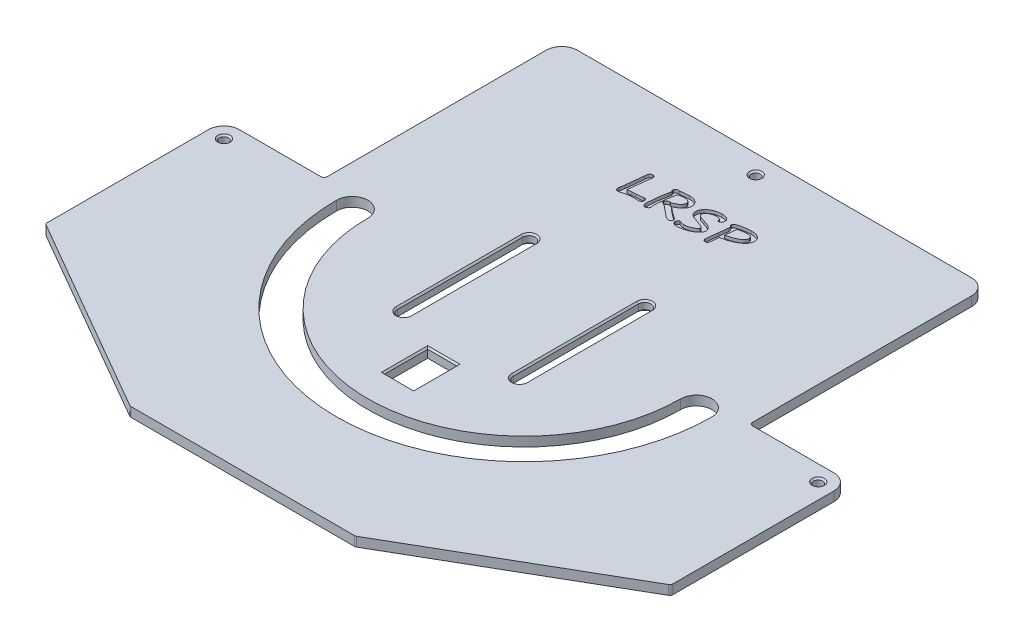
SolidWorks part; units mm, degrees
ref_plane "前视基准面" through (0, 0, 0) normal (0, 0, 1) x (1, 0, 0)
ref_plane "上视基准面" through (0, 0, 0) normal (0, 1, 0) x (1, 0, 0)
ref_plane "右视基准面" through (0, 0, 0) normal (1, 0, 0) x (0, 0, -1)
other "Configuration Table"
sketch "草图1" plane through (0, 0, 0) normal (0, 1, 0) x (1, 0, 0)
  line L11 (-100, -81) -> (-100, -132.4722)
  line L12 (-99.5, -133.3383) -> (-36.2321, -169.866)
  line L13 (-35.7321, -170) -> (35.7321, -170)
  line L14 (36.2321, -169.866) -> (99.5, -133.3383)
  line L15 (100, -132.4722) -> (100, -81)
  line L16 (95, -76) -> (69, -76)
  line L17 (68, -75) -> (68, -5)
  line L18 (63, 0) -> (-63, 0)
  line L19 (-68, -5) -> (-68, -75)
  line L20 (-69, -76) -> (-95, -76)
  circle A13 centre (95, -81) radius 1.45
  circle A14 centre (0, -6) radius 1.45
  circle A15 centre (-95, -81) radius 1.45
  arc A16 (-100, -132.4722) -> (-99.5, -133.3383) centre (-99, -132.4722) ccw
  arc A17 (-36.2321, -169.866) -> (-35.7321, -170) centre (-35.7321, -169) ccw
  arc A18 (35.7321, -170) -> (36.2321, -169.866) centre (35.7321, -169) ccw
  arc A19 (99.5, -133.3383) -> (100, -132.4722) centre (99, -132.4722) ccw
  arc A20 (100, -81) -> (95, -76) centre (95, -81) ccw
  arc A21 (68, -75) -> (69, -76) centre (69, -75) ccw
  arc A22 (68, -5) -> (63, 0) centre (63, -5) ccw
  arc A23 (-63, 0) -> (-68, -5) centre (-63, -5) ccw
  arc A24 (-69, -76) -> (-68, -75) centre (-69, -75) ccw
  arc A25 (-95, -76) -> (-100, -81) centre (-95, -81) ccw
  point P31 (0, 0)
  point P35 (0, -10.6841)
  dimension "D1" = 6
  dimension "D2" = 81
extrude "凸台-拉伸1" add sketch "草图1" along normal blind 3
sketch "草图2" plane through (0, 0, 0) normal (0, 1, 0) x (1, 0, 0)
  line L5 (18.5, -60) -> (18.5, -100) construction
  line L6 (16.5, -60) -> (16.5, -100)
  line L7 (-18.5, -60) -> (-18.5, -100) construction
  line L8 (-16.5, -60) -> (-16.5, -100)
  line L9 (-20.5, -60) -> (-20.5, -100)
  line L10 (0, 0) -> (0, -114.9246) construction
  line L11 (20.5, -60) -> (20.5, -100)
  arc A4 (-16.5, -60) -> (-20.5, -60) centre (-18.5, -60) ccw
  arc A5 (-20.5, -100) -> (-16.5, -100) centre (-18.5, -100) ccw
  arc A6 (16.5, -60) -> (20.5, -60) centre (18.5, -60) cw
  arc A7 (20.5, -100) -> (16.5, -100) centre (18.5, -100) cw
  point P3 (-18.5, -80)
  point P7 (18.5, -80)
  dimension "D2" = 37
  dimension "D3" = 80
  dimension "D11" = 4
  dimension "D12" = 40
extrude "切除-拉伸1" cut sketch "草图2" along normal through all
sketch "草图3" plane through (0, 0, 0) normal (0, 1, 0) x (1, 0, 0)
  text T0 "LRSP" font "Segoe Print" height 10
extrude "切除-拉伸2" cut sketch "草图3" against normal blind 1 from surface at 3 starting at face at (0, 3, 7.45)
sketch "草图4" plane through (0, 0, 0) normal (0, 1, 0) x (1, 0, 0)
  line L0 (0, 0) -> (0, -135) construction
  line L2 (63, 0) -> (-63, 0) construction
  arc A1 (-55, -80) -> (55, -80) centre (0, -80) ccw construction
  circle A6 centre (0, -80) radius 55 construction
  arc A7 (-60, -80) -> (60, -80) centre (0, -80) ccw
  arc A8 (-50, -80) -> (50, -80) centre (0, -80) ccw
  arc A9 (-50, -80) -> (-60, -80) centre (-55, -80) ccw
  arc A10 (60, -80) -> (50, -80) centre (55, -80) ccw
  point P5 (0, -135)
  dimension "D1" = 110
  dimension "D4" = 180
  dimension "D5" = 55
  dimension "D2" = 80
  dimension "D3" = 10
extrude "切除-拉伸3" cut sketch "草图4" along normal through all
sketch "草图5" plane through (0, 0, 0) normal (0, 1, 0) x (1, 0, 0)
  line L0 (4.65, -120) -> (4.65, -106.2)
  line L1 (4.65, -106.2) -> (-4.65, -106.2)
  line L2 (-4.65, -106.2) -> (-4.65, -120)
  line L3 (-4.65, -120) -> (4.65, -120)
  dimension "D1" = 13.8
  dimension "D2" = 9.3
  dimension "D3" = 4.65
  dimension "D4" = 120
  dimension "D5" = 106.2
extrude "切除-拉伸4" cut sketch "草图5" along normal through all
chamfer "倒角1" distance 0.5 angle 45 23 edges at (20.5, 0, 80) (18.5, 0, 58) (18.5, 0, 102) (16.5, 0, 80) (-16.5, 0, 80) (-18.5, 0, 58) (-18.5, 0, 102) (-20.5, 0, 80) (16.5, 3, 80) (18.5, 3, 102) (18.5, 3, 58) (20.5, 3, 80) (-20.5, 3, 80) (-18.5, 3, 102) (-18.5, 3, 58) (-16.5, 3, 80) (0, 3, 120) (4.65, 3, 113.1) (0, 3, 106.2) (-4.65, 3, 113.1) (95, 3, 82.45) (-95, 3, 82.45) (0, 3, 7.45)
